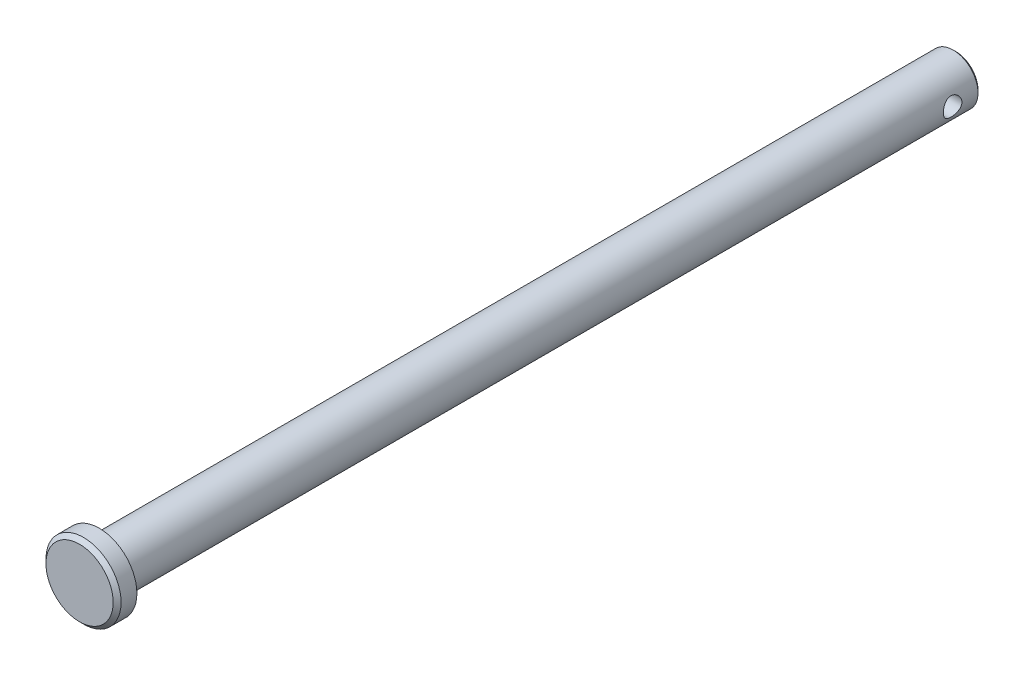
SolidWorks part; units mm, degrees
ref_plane "Front" through (0, 0, 0) normal (0, 0, 1) x (1, 0, 0)
ref_plane "Top" through (0, 0, 0) normal (0, 1, 0) x (1, 0, 0)
ref_plane "Right" through (0, 0, 0) normal (1, 0, 0) x (0, 0, -1)
sketch "Sketch1" plane through (0, 0, 0) normal (0, 0, 1) x (1, 0, 0)
  circle A0 centre (0, 0) radius 3.175
  point P3 (0, 3.175)
  point P4 (0, -3.175)
  dimension "dia" = 6.35
extrude "Extrude1" add sketch "Sketch1" along normal mid plane 110
sketch "Sketch2" plane through (0, 0, 55) normal (0, 0, 1) x (1, 0, 0)
  circle A0 centre (0, 0) radius 4.826
  dimension "head dia" = 9.652
extrude "Extrude2" add sketch "Sketch2" along normal blind 2.54
chamfer "Chamfer1" distance 0.508 angle 45 1 edges at (4.826, 0, 57.54)
sketch "Sketch3" plane through (0, 0, 0) normal (1, 0, 0) x (0, 0, -1)
  line L1 (55, -3.175) -> (55, 3.175) construction
  circle A0 centre (51.4249, 0) radius 1.1906
  point P2 (50.2343, 0)
  dimension "D1" = 3.575
  dimension "hole dia" = 2.3813
extrude "Extrude3" cut sketch "Sketch3" against normal through all and the other way through all
chamfer "Chamfer2" distance 0.3175 angle 45 1 edges at (3.175, 0, -55)
ref_plane "Plane1" through (0, 0, -51.4249) normal (0, 0, 1) x (1, 0, 0)
sketch "Sketch8" plane through (0, 0, 0) normal (1, 0, 0) x (0, 0, -1)
  line L0 (-57.54, 4.318) -> (-57.54, -4.318) construction
  line L1 (-57.032, -4.826) -> (-55, -4.826) construction
  line L2 (55, -2.8575) -> (55, 2.8575) construction
  point P0 (-57.54, 4.826)
  point P1 (-55, 4.826)
  point P5 (55, 3.175)
  point P8 (-57.54, -4.826)
  point P9 (55, -3.175)
equation "\"D1@Chamfer1\" = \"head ht@Extrude2\" * .2"
equation "\"D1@Chamfer2\" = \"dia@Sketch1\" * .05"
